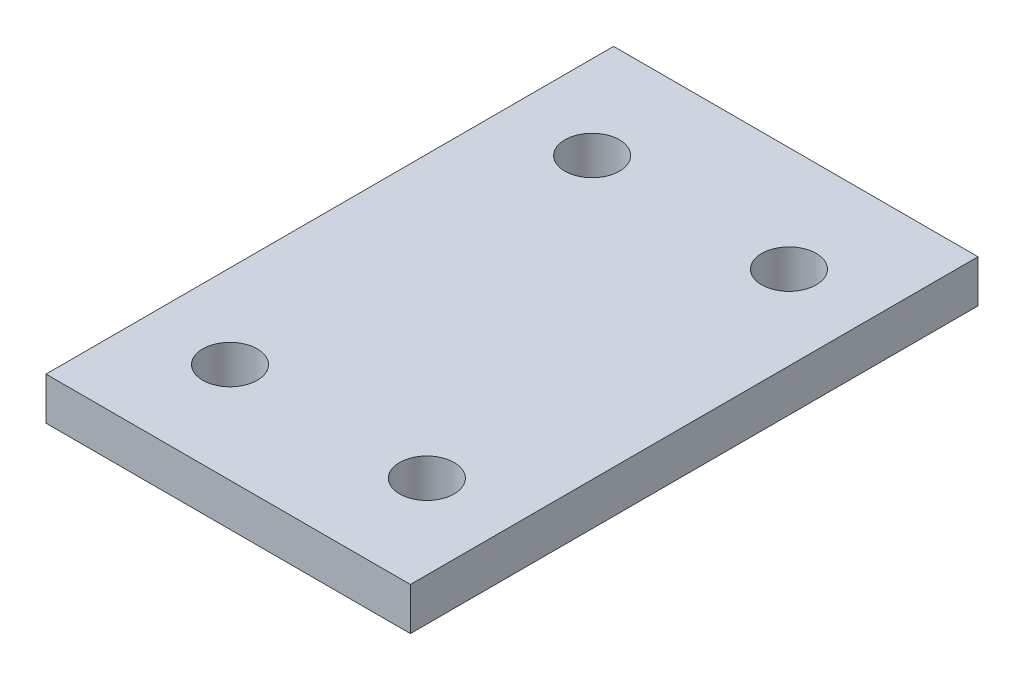
SolidWorks part; units mm, degrees
ref_plane "Front Plane" through (0, 0, 0) normal (0, 0, 1) x (1, 0, 0)
ref_plane "Top Plane" through (0, 0, 0) normal (0, 1, 0) x (1, 0, 0)
ref_plane "Right Plane" through (0, 0, 0) normal (1, 0, 0) x (0, 0, -1)
sketch "Sketch1" plane through (0, 0, 0) normal (0, 1, 0) x (1, 0, 0)
  line L0 (0, -1000) -> (0, 49000) construction
  line L1 (-20.3835, -31.75) -> (20.3835, -31.75)
  line L2 (-20.3835, -31.75) -> (-20.3835, 31.75)
  line L3 (-20.3835, 31.75) -> (20.3835, 31.75)
  line L4 (20.3835, -31.75) -> (20.3835, 31.75)
  line L5 (-20.3835, -31.75) -> (20.3835, 31.75) construction
  line L6 (-20.3835, 31.75) -> (20.3835, -31.75) construction
  circle A0 centre (11.0109, 19.9771) radius 3.05
  circle A1 centre (11.0109, -20.5359) radius 3.05
  circle A2 centre (-11.0109, -20.5359) radius 3.05
  circle A3 centre (-11.0109, 19.9771) radius 3.05
  point P0 (0, 0)
  dimension "D3" = 6.1
  dimension "D1" = 40.767
  dimension "D2" = 22.0218
  dimension "D4" = 40.513
  dimension "D5" = 63.5
  dimension "D6" = 11.2141
extrude "Boss-Extrude1" add sketch "Sketch1" along normal blind 4.7625
